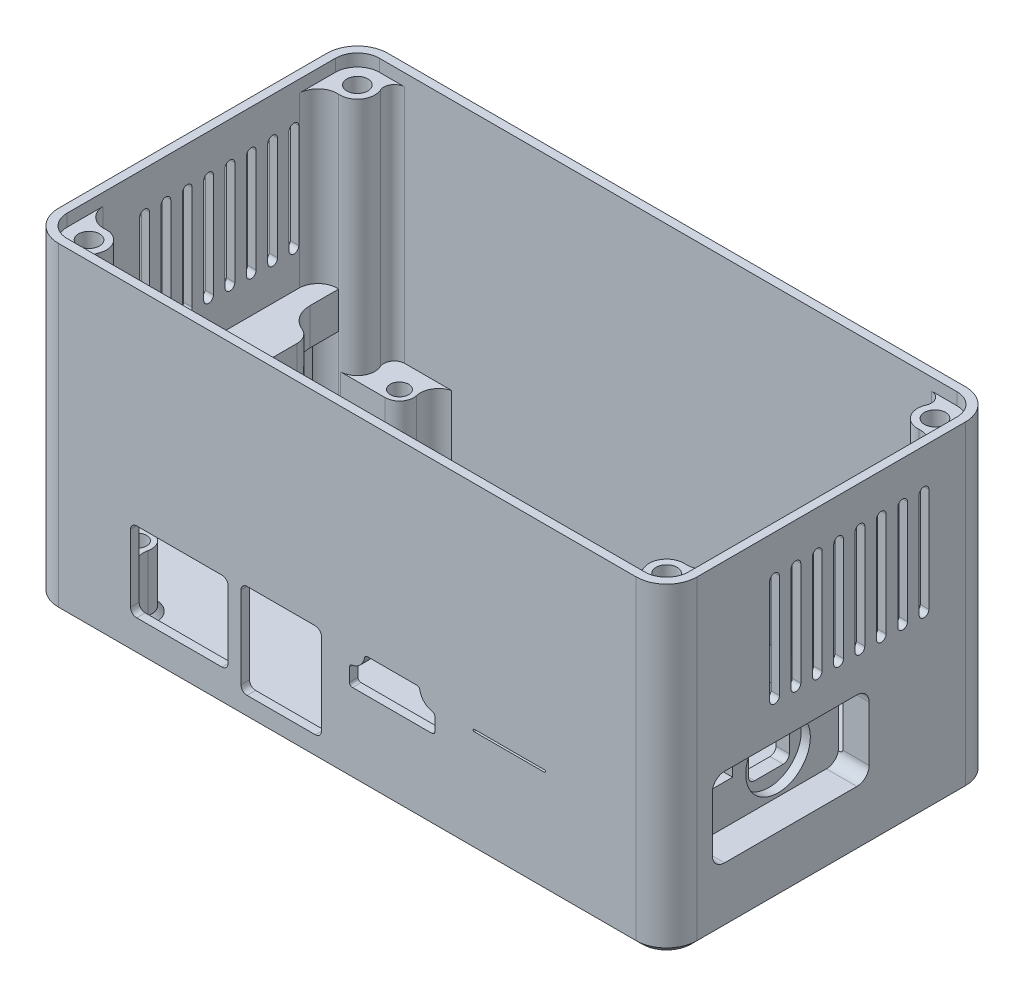
SolidWorks part; units mm, degrees
ref_plane "前视基准面" through (0, 0, 0) normal (0, 0, 1) x (1, 0, 0)
ref_plane "上视基准面" through (0, 0, 0) normal (0, 1, 0) x (1, 0, 0)
ref_plane "右视基准面" through (0, 0, 0) normal (1, 0, 0) x (0, 0, -1)
sketch "草图1" plane through (0, 0, 0) normal (0, 1, 0) x (1, 0, 0)
  line L1 (47.35, -27) -> (-47.35, -27)
  line L2 (52.35, -22) -> (52.35, 22)
  line L3 (47.35, 27) -> (-47.35, 27)
  line L4 (-52.35, -22) -> (-52.35, 22)
  line L5 (52.35, -27) -> (-52.35, 27) construction
  line L6 (52.35, 27) -> (-52.35, -27) construction
  arc A0 (52.35, -22) -> (47.35, -27) centre (47.35, -22) cw
  arc A1 (-47.35, -27) -> (-52.35, -22) centre (-47.35, -22) cw
  arc A2 (52.35, 22) -> (47.35, 27) centre (47.35, 22) ccw
  arc A3 (-47.35, 27) -> (-52.35, 22) centre (-47.35, 22) ccw
  point P0 (0, 0)
  dimension "D3" = 5
  dimension "D1" = 104.7
  dimension "D2" = 54
extrude "凸台-拉伸1" add sketch "草图1" along normal blind 52.66
shell "抽壳1" thickness 1.4
sketch "草图2" plane through (0, 1.4, 0) normal (0, 1, 0) x (1, 0, 0)
  line L0 (47.35, 25.6) -> (-47.35, 25.6) construction
  line L1 (47.35, 25.6) -> (-47.35, 25.6) construction
  line L2 (-50.95, 22) -> (-50.95, -22) construction
  line L3 (-50.95, 22) -> (-50.95, -22) construction
  line L4 (-43.1902, 25.6) -> (-47.35, 25.6)
  line L5 (-50.95, 22) -> (-50.95, 15.8763)
  arc A0 (-43.1902, 25.6) -> (-44.7392, 23.1641) centre (-43.1581, 23.8691) ccw
  arc A1 (-44.7392, 23.1641) -> (-47.5608, 19.1492) centre (-47.35, 22) cw
  arc A2 (-47.5608, 19.1492) -> (-50.95, 15.8763) centre (-47.7938, 15.9992) ccw
  circle A3 centre (-47.35, 22) radius 1.7237
  arc A4 (-47.35, 25.6) -> (-50.95, 22) centre (-47.35, 22) ccw construction
  arc A5 (-47.35, 25.6) -> (-50.95, 22) centre (-47.35, 22) ccw
  line M5 (47.35, 25.6) -> (-47.35, 25.6)
  arc M6 (-47.35, 25.6) -> (-50.95, 22) centre (-47.35, 22) ccw
  line M7 (-50.95, 22) -> (-50.95, -22)
extrude "凸台-拉伸2" add sketch "草图2" along normal offset from surface (49.26 mm away) 2 contours A2 A1 A0 A3 M5 M6 M7 up to face at (0, 52.66, 0)
mirror "镜向1" about plane through (0, 0, 0) normal (1, 0, 0) of "凸台-拉伸2"
mirror "镜向2" about plane through (0, 0, 0) normal (0, 0, 1) of "镜向1", "凸台-拉伸2"
sketch "草图3" plane through (0, 1.4, 0) normal (0, 1, 0) x (1, 0, 0)
  line L0 (-47.2955, 19.1419) -> (-39.925, 19.1419)
  line L4 (0, -28.963) -> (0, 28.963) construction
  line L5 (43.1902, 25.6) -> (-43.1902, 25.6) construction
  line L6 (47.2955, 19.1419) -> (39.925, 19.1419)
  line L7 (-28.963, 0) -> (28.963, 0) construction
  line L8 (47.2955, -19.1419) -> (39.925, -19.1419)
  line L9 (-47.2955, -19.1419) -> (-39.925, -19.1419)
  arc A0 (-47.5608, 19.1492) -> (-44.7392, 23.1641) centre (-47.35, 22) ccw construction
  arc A1 (-47.5608, 19.1492) -> (-44.7392, 23.1641) centre (-47.35, 22) ccw construction
  arc A2 (-39.925, 19.1419) -> (-37.6532, 22.0062) centre (-39.925, 21.475) ccw
  arc A3 (-37.6532, 22.0062) -> (-35.4808, 25.6) centre (-34.7265, 22.6906) cw
  circle A4 centre (39.925, 21.475) radius 1.5
  arc A5 (39.925, 19.1419) -> (37.6532, 22.0062) centre (39.925, 21.475) cw
  circle A6 centre (-39.925, 21.475) radius 1.5
  arc A7 (37.6532, 22.0062) -> (35.4808, 25.6) centre (34.7265, 22.6906) ccw
  circle A8 centre (39.925, -21.475) radius 1.5
  arc A9 (39.925, -19.1419) -> (37.6532, -22.0062) centre (39.925, -21.475) ccw
  arc A10 (37.6532, -22.0062) -> (35.4808, -25.6) centre (34.7265, -22.6906) cw
  circle A11 centre (-39.925, -21.475) radius 1.5
  arc A12 (-37.6532, -22.0062) -> (-35.4808, -25.6) centre (-34.7265, -22.6906) ccw
  arc A13 (-39.925, -19.1419) -> (-37.6532, -22.0062) centre (-39.925, -21.475) cw
  arc M5 (-44.7392, -23.1641) -> (-43.1902, -25.6) centre (-43.1581, -23.8691) ccw
  line M6 (-43.1902, -25.6) -> (43.1902, -25.6)
  arc M7 (43.1902, -25.6) -> (44.7392, -23.1641) centre (43.1581, -23.8691) ccw
  arc M8 (44.7392, -23.1641) -> (47.5608, -19.1492) centre (47.35, -22) cw
  arc M12 (47.5608, 19.1492) -> (44.7392, 23.1641) centre (47.35, 22) cw
  arc M13 (44.7392, 23.1641) -> (43.1902, 25.6) centre (43.1581, 23.8691) ccw
  line M14 (43.1902, 25.6) -> (-43.1902, 25.6)
  arc M15 (-43.1902, 25.6) -> (-44.7392, 23.1641) centre (-43.1581, 23.8691) ccw
  arc M16 (-44.7392, 23.1641) -> (-47.5608, 19.1492) centre (-47.35, 22) cw
  arc M20 (-47.5608, -19.1492) -> (-44.7392, -23.1641) centre (-47.35, -22) cw
  dimension "D1" = 3
  dimension "D2" = 79.85
  dimension "D3" = 42.95
extrude "凸台-拉伸3" add sketch "草图3" along normal blind 10 contours A2 A3 L0 A6 M14 M15 M16 | A13 L9 A12 A11 M20 M5 M6 | A7 A5 L6 A4 M12 M13 M14 | A9 A10 L8 A8 M6 M7 M8
sketch "草图4" plane through (0, 1.4, 0) normal (0, 1, 0) x (1, 0, 0)
  line L0 (-47.5608, 19.1492) -> (-47.5608, 14.4215)
  line L2 (-43.25, 8.0277) -> (-43.25, -8.0277)
  line L3 (-59.9708, 0) -> (65.8474, 0) construction
  line L4 (-47.5608, -19.1492) -> (-47.5608, -14.4215)
  line L5 (-50.95, 22) -> (-50.95, -22) construction
  line L6 (50.95, 10.4123) -> (50.95, 9.6247)
  line L7 (50.95, -16.122) -> (50.95, 16.122) construction
  line L8 (43.68, 3.5009) -> (43.68, -7.6236)
  line L9 (45.8738, -11.0505) -> (45.8738, -19.5521)
  line L11 (50.95, -22) -> (50.95, 22) construction
  line L12 (-50.95, 16.122) -> (-50.95, -16.122) construction
  line L13 (50.95, -16.122) -> (50.95, 16.122)
  line L14 (-50.95, 16.122) -> (-50.95, -16.122)
  arc A0 (47.2955, -19.1419) -> (44.7392, -23.1641) centre (47.35, -22) ccw construction
  arc A1 (-47.5608, 14.4215) -> (-44.8869, 10.4555) centre (-43.2826, 14.4215) ccw
  arc A2 (-44.8869, 10.4555) -> (-43.25, 8.0277) centre (-45.869, 8.0277) cw
  arc A3 (-47.5608, -14.4215) -> (-44.8869, -10.4555) centre (-43.2826, -14.4215) cw
  arc A4 (-44.8869, -10.4555) -> (-43.25, -8.0277) centre (-45.869, -8.0277) ccw
  arc A5 (50.95, 9.6247) -> (46.8908, 6.2055) centre (47.4804, 9.6247) cw
  arc A6 (46.8908, 6.2055) -> (43.68, 3.5009) centre (46.4245, 3.5009) ccw
  arc A7 (43.68, -7.6236) -> (44.9554, -9.6159) centre (45.8738, -7.6236) ccw
  arc A8 (44.9554, -9.6159) -> (45.8738, -11.0505) centre (44.294, -11.0505) cw
  arc A10 (-50.95, -16.122) -> (-47.5608, -19.1492) centre (-47.7938, -15.9992) ccw construction
  arc A11 (-47.5608, 19.1492) -> (-50.95, 16.122) centre (-47.7938, 15.9992) ccw construction
  arc A13 (-50.95, -16.122) -> (-47.5608, -19.1492) centre (-47.7938, -15.9992) ccw
  arc A14 (-47.5608, 19.1492) -> (-50.95, 16.122) centre (-47.7938, 15.9992) ccw
  arc A15 (47.5608, -19.1492) -> (50.95, -16.122) centre (47.7938, -15.9992) ccw construction
  arc A16 (47.5608, -19.1492) -> (44.7392, -23.1641) centre (47.35, -22) ccw construction
  arc A17 (47.5608, -19.1492) -> (50.95, -16.122) centre (47.7938, -15.9992) ccw
  arc A18 (47.5608, -19.1492) -> (45.8738, -19.5521) centre (47.35, -22) ccw
  point P22 (-43.25, 0)
  arc M10 (47.5608, -19.1492) -> (50.95, -16.122) centre (47.7938, -15.9992) ccw
  line M11 (50.95, -16.122) -> (50.95, 16.122)
  arc M22 (-47.5608, 19.1492) -> (-50.95, 16.122) centre (-47.7938, 15.9992) ccw
  line M23 (-50.95, 16.122) -> (-50.95, -16.122)
  arc M24 (-50.95, -16.122) -> (-47.5608, -19.1492) centre (-47.7938, -15.9992) ccw
  dimension "D1" = 7.7
  dimension "D2" = 86.93
extrude "凸台-拉伸4" add sketch "草图4" along normal blind 21.6 contours L3 L14 L4 A3 A4 L2 M24 | L3 L2 A2 A1 L0 M23 M22 | L3 A6 L8 A7 A8 L9 M10 M11 | A6 L3 L13 A5
sketch "草图5" plane through (0, 1.4, 0) normal (0, 1, 0) x (1, 0, 0)
  line L0 (50.95, -16.122) -> (50.95, 16.122) construction
  line L1 (45.8738, -11.0505) -> (45.8738, -19.5521) construction
  line L2 (43.68, 3.5009) -> (43.68, -7.6236) construction
  line L3 (50.95, 10.4123) -> (50.95, 9.6247) construction
  line L4 (-50.95, 16.122) -> (-50.95, -16.122)
  line L5 (-47.5608, -19.1492) -> (-47.5608, -14.4215)
  line L6 (-43.25, -8.0277) -> (-43.25, 8.0277)
  line L7 (-47.5608, 14.4215) -> (-47.5608, 19.1492)
  line L9 (-47.5608, -19.1492) -> (-47.5608, -14.4215)
  line L10 (-43.25, -8.0277) -> (-43.25, 8.0277)
  line L11 (-47.5608, 14.4215) -> (-47.5608, 19.1492)
  line L12 (50.95, -16.122) -> (50.95, 16.122)
  line L13 (45.8738, -11.0505) -> (45.8738, -19.5521)
  line L14 (43.68, 3.5009) -> (43.68, -7.6236)
  line L15 (50.95, 10.4123) -> (50.95, 9.6247)
  line L16 (-50.45, 17.7083) -> (-50.45, -17.7083)
  line L17 (-50.95, 22) -> (-50.95, -22) construction
  arc A1 (45.8738, -11.0505) -> (44.9554, -9.6159) centre (44.294, -11.0505) ccw construction
  arc A2 (43.68, -7.6236) -> (44.9554, -9.6159) centre (45.8738, -7.6236) ccw construction
  arc A3 (46.8908, 6.2055) -> (43.68, 3.5009) centre (46.4245, 3.5009) ccw construction
  arc A4 (46.8908, 6.2055) -> (50.95, 9.6247) centre (47.4804, 9.6247) ccw construction
  arc A6 (-50.95, -16.122) -> (-47.5608, -19.1492) centre (-47.7938, -15.9992) ccw
  arc A7 (-44.8869, -10.4555) -> (-47.5608, -14.4215) centre (-43.2826, -14.4215) ccw
  arc A8 (-44.8869, -10.4555) -> (-43.25, -8.0277) centre (-45.869, -8.0277) ccw
  arc A9 (-43.25, 8.0277) -> (-44.8869, 10.4555) centre (-45.869, 8.0277) ccw
  arc A10 (-47.5608, 14.4215) -> (-44.8869, 10.4555) centre (-43.2826, 14.4215) ccw
  arc A11 (-47.5608, 19.1492) -> (-50.95, 16.122) centre (-47.7938, 15.9992) ccw
  arc A13 (-44.8869, -10.4555) -> (-47.5608, -14.4215) centre (-43.2826, -14.4215) ccw
  arc A14 (-44.8869, -10.4555) -> (-43.25, -8.0277) centre (-45.869, -8.0277) ccw
  arc A15 (-43.25, 8.0277) -> (-44.8869, 10.4555) centre (-45.869, 8.0277) ccw
  arc A16 (-47.5608, 14.4215) -> (-44.8869, 10.4555) centre (-43.2826, 14.4215) ccw
  arc A17 (-47.5608, 19.1492) -> (-50.45, 17.7083) centre (-47.7938, 15.9992) ccw
  arc A18 (45.8738, -11.0505) -> (44.9554, -9.6159) centre (44.294, -11.0505) ccw
  arc A19 (43.68, -7.6236) -> (44.9554, -9.6159) centre (45.8738, -7.6236) ccw
  arc A20 (46.8908, 6.2055) -> (43.68, 3.5009) centre (46.4245, 3.5009) ccw
  arc A21 (46.8908, 6.2055) -> (50.95, 9.6247) centre (47.4804, 9.6247) ccw
  arc A22 (-50.95, -16.122) -> (-47.5608, -19.1492) centre (-47.7938, -15.9992) ccw construction
  arc A23 (-50.45, -17.7083) -> (-47.5608, -19.1492) centre (-47.7938, -15.9992) ccw
  line M24 (-47.5608, 19.1492) -> (-47.5608, 14.4215)
  arc M25 (-47.5608, 14.4215) -> (-44.8869, 10.4555) centre (-43.2826, 14.4215) ccw
  arc M26 (-44.8869, 10.4555) -> (-43.25, 8.0277) centre (-45.869, 8.0277) cw
  line M27 (-43.25, 8.0277) -> (-43.25, -8.0277)
  arc M28 (-43.25, -8.0277) -> (-44.8869, -10.4555) centre (-45.869, -8.0277) cw
  arc M29 (-44.8869, -10.4555) -> (-47.5608, -14.4215) centre (-43.2826, -14.4215) ccw
  line M30 (-47.5608, -14.4215) -> (-47.5608, -19.1492)
  dimension "D2" = 0.5
  dimension "D1" = 0
extrude "切除-拉伸1" cut sketch "草图5" along normal offset from surface (15.6 mm away) 6 contours L16 A23 A17 M30 M29 M28 M27 M26 M25 M24 up to face at (-47.0172, 23, 0)
chamfer "倒角1" distance 1 angle 45 8 edges at (-52.35, 0, 0) (0, 0, -27) (52.35, 0, 0) (-50.8855, 0, -25.5355) (50.8855, 0, -25.5355) (-50.8855, 0, 25.5355) (50.8855, 0, 25.5355) (0, 0, 27)
sketch "草图6" plane through (52.35, 0, 0) normal (1, 0, 0) x (0, 0, -1)
  line L0 (22, 0) -> (-22, 0) construction
  line L1 (4.2, 9.8) -> (-17.5, 9.8)
  line L2 (6.2, 11.8) -> (6.2, 20.8)
  line L3 (4.2, 22.8) -> (-17.5, 22.8)
  line L4 (-19.5, 11.8) -> (-19.5, 20.8)
  line L5 (6.2, 9.8) -> (-19.5, 22.8) construction
  line L6 (6.2, 22.8) -> (-19.5, 9.8) construction
  line L7 (-27, 52.66) -> (-27, 1) construction
  arc A0 (4.2, 9.8) -> (6.2, 11.8) centre (4.2, 11.8) ccw
  arc A1 (-19.5, 20.8) -> (-17.5, 22.8) centre (-17.5, 20.8) cw
  arc A2 (-19.5, 11.8) -> (-17.5, 9.8) centre (-17.5, 11.8) ccw
  arc A3 (6.2, 20.8) -> (4.2, 22.8) centre (4.2, 20.8) ccw
  point P0 (-6.65, 16.3)
  dimension "D1" = 2
  dimension "D2" = 9.8
  dimension "D3" = 7.5
  dimension "D4" = 25.7
  dimension "D5" = 13
extrude "切除-拉伸2" cut sketch "草图6" against normal blind 5
sketch "草图7" plane through (47.35, 0, 0) normal (1, 0, 0) x (0, 0, -1)
  line L0 (-17.8, 16.3) -> (-11.18, 16.3)
  line L1 (-12.58, 18.6) -> (-16.4, 18.6)
  line L2 (-17.8, 16.3) -> (-17.8, 17.78)
  line L3 (-11.18, 16.3) -> (-11.18, 17.78)
  line L4 (-17.8, 17.78) -> (-16.4, 18.6)
  line L5 (-12.58, 18.6) -> (-11.18, 17.78)
  line L6 (-27, 52.66) -> (-27, 1) construction
  line L9 (-17.5, 9.8) -> (4.2, 9.8) construction
  circle A0 centre (-3.73, 15.65) radius 5.3
  dimension "D1" = 10.6
  dimension "D2" = 2.3
  dimension "D3" = 1.48
  dimension "D4" = 1.48
  dimension "D5" = 1.4
  dimension "D6" = 1.4
  dimension "D7" = 7.45
  dimension "D8" = 9.2
  dimension "D9" = 2.95
  dimension "D10" = 6.5
  dimension "D11" = 6.62
extrude "切除-拉伸3" cut sketch "草图7" against normal blind 1.5
sketch "草图8" plane through (45.85, 0, 0) normal (1, 0, 0) x (0, 0, -1)
  line L1 (-6.08, 18.8) -> (-1.38, 18.8)
  line L2 (-7.08, 17.8) -> (-7.08, 13.5)
  line L3 (-6.08, 12.5) -> (-1.38, 12.5)
  line L4 (-0.38, 17.8) -> (-0.38, 13.5)
  line L5 (-7.08, 18.8) -> (-0.38, 12.5) construction
  line L6 (-7.08, 12.5) -> (-0.38, 18.8) construction
  arc A0 (-7.08, 17.8) -> (-6.08, 18.8) centre (-6.08, 17.8) cw
  arc A1 (-0.38, 17.8) -> (-1.38, 18.8) centre (-1.38, 17.8) ccw
  arc A2 (-1.38, 12.5) -> (-0.38, 13.5) centre (-1.38, 13.5) ccw
  arc A3 (-6.08, 12.5) -> (-7.08, 13.5) centre (-6.08, 13.5) cw
  point P0 (-3.73, 15.65)
  dimension "D1" = 1
  dimension "D2" = 6.3
  dimension "D3" = 6.7
extrude "切除-拉伸4" cut sketch "草图8" against normal blind 22
sketch "草图9" plane through (0, 0, 27) normal (0, 0, 1) x (1, 0, 0)
  line L1 (-34.55, 18.95) -> (-20.55, 18.95)
  line L2 (-35.55, 17.95) -> (-35.55, 6.9)
  line L3 (-34.55, 5.9) -> (-20.55, 5.9)
  line L4 (-19.55, 17.95) -> (-19.55, 6.9)
  line L5 (-35.55, 18.95) -> (-19.55, 5.9) construction
  line L6 (-35.55, 5.9) -> (-19.55, 18.95) construction
  line L7 (-44.65, 18.5677) -> (-44.65, 12.1279)
  line L8 (-52.35, 52.66) -> (-52.35, 1) construction
  line L9 (47.35, 0) -> (-47.35, 0) construction
  line L10 (3.308, 19.3) -> (11.392, 19.3)
  line L11 (-16.44, 3.94) -> (-5.25, 3.94)
  line L12 (-17.44, 4.94) -> (-17.44, 18.41)
  line L13 (-16.44, 19.41) -> (-5.25, 19.41)
  line L14 (-4.25, 4.94) -> (-4.25, 18.41)
  line L15 (0.85, 13.7) -> (13.85, 13.7)
  line L16 (0.35, 14.2) -> (0.35, 16.342)
  line L18 (14.35, 14.2) -> (14.35, 16.342)
  line L19 (20.8117, 17.575) -> (32.3117, 17.575) construction
  line L20 (20.8117, 17.75) -> (32.3117, 17.75)
  line L21 (20.8117, 17.4) -> (32.3117, 17.4)
  arc A0 (-19.55, 17.95) -> (-20.55, 18.95) centre (-20.55, 17.95) ccw
  arc A1 (-19.55, 6.9) -> (-20.55, 5.9) centre (-20.55, 6.9) cw
  arc A2 (-34.55, 5.9) -> (-35.55, 6.9) centre (-34.55, 6.9) cw
  arc A3 (-34.55, 18.95) -> (-35.55, 17.95) centre (-34.55, 17.95) ccw
  arc A4 (0.7667, 16.835) -> (2.815, 18.8833) centre (0.35, 19.3) ccw
  arc A5 (11.885, 18.8833) -> (13.9333, 16.835) centre (14.35, 19.3) ccw
  arc A6 (-4.25, 4.94) -> (-5.25, 3.94) centre (-5.25, 4.94) cw
  arc A7 (-16.44, 3.94) -> (-17.44, 4.94) centre (-16.44, 4.94) cw
  arc A8 (-4.25, 18.41) -> (-5.25, 19.41) centre (-5.25, 18.41) ccw
  arc A9 (-17.44, 18.41) -> (-16.44, 19.41) centre (-16.44, 18.41) cw
  arc A10 (0.85, 13.7) -> (0.35, 14.2) centre (0.85, 14.2) cw
  arc A11 (14.35, 14.2) -> (13.85, 13.7) centre (13.85, 14.2) cw
  arc A12 (14.35, 16.342) -> (13.9333, 16.835) centre (13.85, 16.342) ccw
  arc A13 (0.7667, 16.835) -> (0.35, 16.342) centre (0.85, 16.342) ccw
  arc A14 (11.885, 18.8833) -> (11.392, 19.3) centre (11.392, 18.8) ccw
  arc A15 (2.815, 18.8833) -> (3.308, 19.3) centre (3.308, 18.8) cw
  arc A16 (20.8117, 17.75) -> (20.8117, 17.4) centre (20.8117, 17.575) ccw
  arc A17 (32.3117, 17.4) -> (32.3117, 17.75) centre (32.3117, 17.575) ccw
  point P0 (-27.55, 12.425)
  point P35 (26.5617, 17.575)
  point P41 (-4.25, 3.94)
  point P44 (-17.44, 3.94)
  point P47 (-4.25, 19.41)
  point P52 (0.35, 13.7)
  point P55 (14.35, 13.7)
  point P58 (14.35, 16.8)
  point P61 (0.35, 16.8)
  point P64 (11.85, 19.3)
  point P67 (2.85, 19.3)
  point P71 (20.6367, 17.575)
  dimension "D6" = 1
  dimension "D15" = 2.5
  dimension "D16" = 2.5
  dimension "D19" = 1
  dimension "D20" = 0.5
  dimension "D21" = 0.5
  dimension "D22" = 0.5
  dimension "D1" = 7.7
  dimension "D2" = 16
  dimension "D3" = 9.1
  dimension "D4" = 13.05
  dimension "D5" = 5.9
  dimension "D7" = 2.11
  dimension "D8" = 13.19
  dimension "D9" = 15.47
  dimension "D10" = 3.94
  dimension "D11" = 4.6
  dimension "D12" = 14
  dimension "D13" = 3.1
  dimension "D14" = 3.1
  dimension "D17" = 9
  dimension "D18" = 13.7
  dimension "D23" = 6.2867
  dimension "D24" = 17.4
  dimension "D25" = 11.5
  dimension "D26" = 0.35
extrude "切除-拉伸5" cut sketch "草图9" against normal up to next contours L1 A3 L2 A2 L3 A1 L4 A0 | A9 L12 A7 L11 A6 L14 A8 L13 | A15 A4 A13 L16 A10 L15 A11 L18 A12 A5 A14 L10 | L21 A16 L20 A17
sketch "草图10" plane through (-52.35, 0, 0) normal (-1, 0, 0) x (0, 0, 1)
  line L0 (-15.2, 46.06) -> (-15.2, 29.06) construction
  line L1 (-14.4, 46.06) -> (-14.4, 29.06)
  line L2 (-16, 46.06) -> (-16, 29.06)
  line L3 (-22, 52.66) -> (22, 52.66) construction
  line L4 (-27, 52.66) -> (-27, 1) construction
  line L5 (-11.7, 46.06) -> (-11.7, 29.06) construction
  line L6 (-10.9, 46.06) -> (-10.9, 29.06)
  line L7 (-12.5, 46.06) -> (-12.5, 29.06)
  line L8 (-8.2, 46.06) -> (-8.2, 29.06) construction
  line L9 (-7.4, 46.06) -> (-7.4, 29.06)
  line L10 (-9, 46.06) -> (-9, 29.06)
  line L11 (-4.7, 46.06) -> (-4.7, 29.06) construction
  line L12 (-3.9, 46.06) -> (-3.9, 29.06)
  line L13 (-5.5, 46.06) -> (-5.5, 29.06)
  line L14 (-1.2, 46.06) -> (-1.2, 29.06) construction
  line L15 (-0.4, 46.06) -> (-0.4, 29.06)
  line L16 (-2, 46.06) -> (-2, 29.06)
  line L17 (2.3, 46.06) -> (2.3, 29.06) construction
  line L18 (3.1, 46.06) -> (3.1, 29.06)
  line L19 (1.5, 46.06) -> (1.5, 29.06)
  line L20 (5.8, 46.06) -> (5.8, 29.06) construction
  line L21 (6.6, 46.06) -> (6.6, 29.06)
  line L22 (5, 46.06) -> (5, 29.06)
  line L23 (9.3, 46.06) -> (9.3, 29.06) construction
  line L24 (10.1, 46.06) -> (10.1, 29.06)
  line L25 (8.5, 46.06) -> (8.5, 29.06)
  arc A0 (-14.4, 46.06) -> (-16, 46.06) centre (-15.2, 46.06) ccw
  arc A1 (-16, 29.06) -> (-14.4, 29.06) centre (-15.2, 29.06) ccw
  arc A2 (-10.9, 46.06) -> (-12.5, 46.06) centre (-11.7, 46.06) ccw
  arc A3 (-12.5, 29.06) -> (-10.9, 29.06) centre (-11.7, 29.06) ccw
  arc A4 (-7.4, 46.06) -> (-9, 46.06) centre (-8.2, 46.06) ccw
  arc A5 (-9, 29.06) -> (-7.4, 29.06) centre (-8.2, 29.06) ccw
  arc A6 (-3.9, 46.06) -> (-5.5, 46.06) centre (-4.7, 46.06) ccw
  arc A7 (-5.5, 29.06) -> (-3.9, 29.06) centre (-4.7, 29.06) ccw
  arc A8 (-0.4, 46.06) -> (-2, 46.06) centre (-1.2, 46.06) ccw
  arc A9 (-2, 29.06) -> (-0.4, 29.06) centre (-1.2, 29.06) ccw
  arc A10 (3.1, 46.06) -> (1.5, 46.06) centre (2.3, 46.06) ccw
  arc A11 (1.5, 29.06) -> (3.1, 29.06) centre (2.3, 29.06) ccw
  arc A12 (6.6, 46.06) -> (5, 46.06) centre (5.8, 46.06) ccw
  arc A13 (5, 29.06) -> (6.6, 29.06) centre (5.8, 29.06) ccw
  arc A14 (10.1, 46.06) -> (8.5, 46.06) centre (9.3, 46.06) ccw
  arc A15 (8.5, 29.06) -> (10.1, 29.06) centre (9.3, 29.06) ccw
  point P2 (-15.2, 37.56)
  point P7 (-15.2, 46.86)
  point P8 (-15.2, 28.26)
  point P16 (-11.7, 37.56)
  point P23 (-8.2, 37.56)
  point P30 (-4.7, 37.56)
  point P37 (-1.2, 37.56)
  point P44 (2.3, 37.56)
  point P51 (5.8, 37.56)
  point P58 (9.3, 37.56)
  dimension "D1" = 18.6
  dimension "D2" = 5.8
  dimension "D3" = 1.6
  dimension "D4" = 11
  dimension "D6" = 1.9
  dimension "D5" = 8
extrude "切除-拉伸6" cut sketch "草图10" against normal up to next
mirror "镜向3" about plane through (0, 0, 0) normal (1, 0, 0) of "切除-拉伸6"
sketch "草图11" plane through (0, 0, 0) normal (0, 1, 0) x (1, 0, 0)
  circle A0 centre (-47.35, 22) radius 1.7237
  circle A1 centre (47.35, 22) radius 1.7237
  circle A2 centre (47.35, -22) radius 1.7237
  circle A3 centre (-47.35, -22) radius 1.7237
extrude "切除-拉伸7" cut sketch "草图11" along normal blind 34
sketch "草图13" plane through (0, 0, 0) normal (0, 1, 0) x (1, 0, 0)
  circle A0 centre (-39.925, 21.475) radius 1.5
  circle A1 centre (39.925, 21.475) radius 1.5
  circle A2 centre (39.925, -21.475) radius 1.5
  circle A3 centre (-39.925, -21.475) radius 1.5
extrude "切除-拉伸8" cut sketch "草图13" along normal blind 10
chamfer "倒角2" distance 3 angle 45 4 edges at (39.925, 0, 22.975) (-39.925, 0, 22.975) (-39.925, 0, -19.975) (39.925, 0, -19.975)
